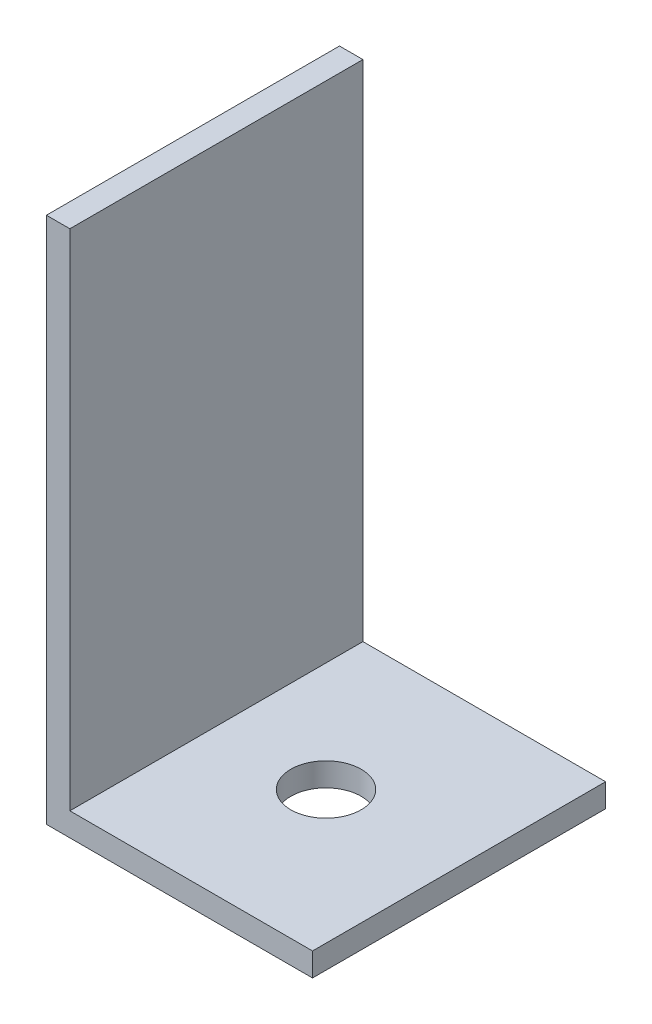
SolidWorks part; units mm, degrees
ref_plane "正面" through (0, 0, 0) normal (0, 0, 1) x (1, 0, 0)
ref_plane "平面" through (0, 0, 0) normal (0, 1, 0) x (1, 0, 0)
ref_plane "右側面" through (0, 0, 0) normal (1, 0, 0) x (0, 0, -1)
sketch "ｽｹｯﾁ1" plane through (0, 0, 0) normal (0, 1, 0) x (1, 0, 0)
  line L0 (11.35, 0) -> (-11.35, 0) construction
  line L1 (11.35, 12.5) -> (-11.35, 12.5)
  line L2 (11.35, 12.5) -> (11.35, -12.5)
  line L3 (11.35, -12.5) -> (-11.35, -12.5)
  line L4 (-11.35, 12.5) -> (-11.35, -12.5)
  line L5 (11.35, 12.5) -> (-11.35, -12.5) construction
  line L6 (11.35, -12.5) -> (-11.35, 12.5) construction
  circle A1 centre (0, 0) radius 3
  point P0 (0, 0)
  dimension "D3" = 6
  dimension "D1" = 22.7
  dimension "D2" = 25
  dimension "D4" = 11.35
extrude "ﾎﾞｽ - 押し出し1" add sketch "ｽｹｯﾁ1" along normal blind 2
sketch "ｽｹｯﾁ2" plane through (0, 2, 0) normal (0, 1, 0) x (1, 0, 0)
  line L0 (-11.35, -12.5) -> (11.35, -12.5) construction
  line L1 (-11.35, 12.5) -> (-9.35, 12.5)
  line L2 (-11.35, 12.5) -> (-11.35, -12.5)
  line L3 (-11.35, -12.5) -> (-9.35, -12.5)
  line L4 (-9.35, 12.5) -> (-9.35, -12.5)
  dimension "D1" = 2
extrude "ﾎﾞｽ - 押し出し2" add sketch "ｽｹｯﾁ2" along normal blind 43
